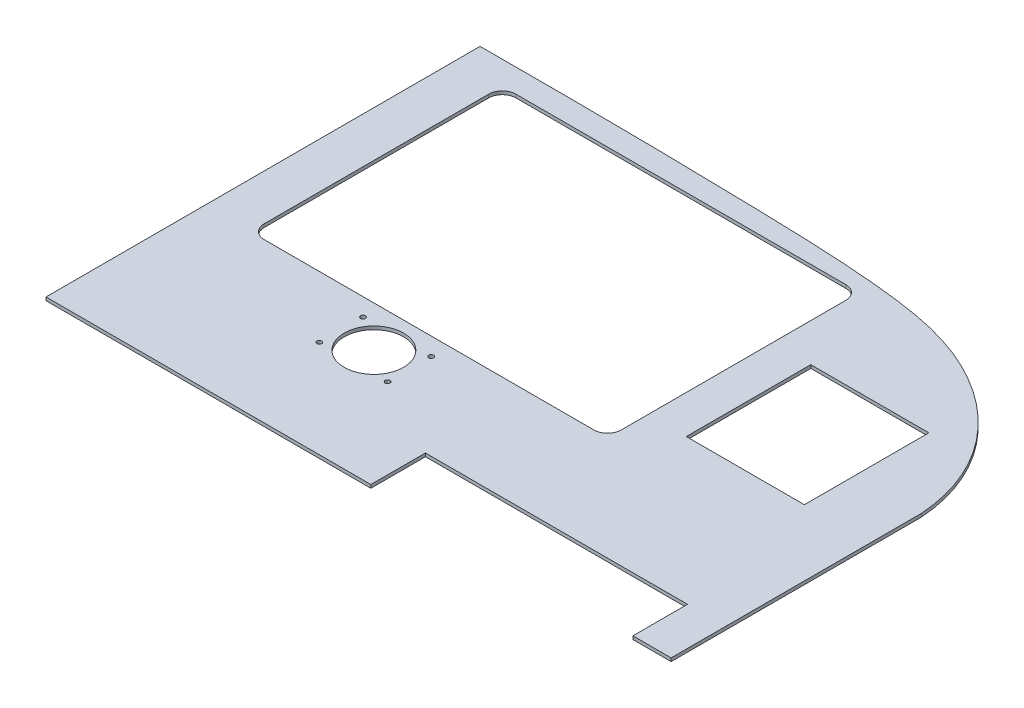
SolidWorks part; units mm, degrees
ref_plane "Alzado" through (0, 0, 0) normal (0, 0, 1) x (1, 0, 0)
ref_plane "Planta" through (0, 0, 0) normal (0, 1, 0) x (1, 0, 0)
ref_plane "Vista lateral" through (0, 0, 0) normal (1, 0, 0) x (0, 0, -1)
sketch "Croquis1" plane through (0, 0, 0) normal (0, 1, 0) x (1, 0, 0)
  line L0 (-872.7705, -164.3587) -> (-420.2125, -164.3587) construction
  line L1 (-420.2125, -164.3587) -> (-420.2125, 152.6413) construction
  line L2 (-599.3125, -124.3587) -> (-545.2125, -124.3587) construction
  line L3 (-599.3125, -124.3587) -> (-599.3125, -47.6587) construction
  line L4 (-599.3125, -47.6587) -> (-545.2125, -47.6587) construction
  line L5 (-545.2125, -124.3587) -> (-545.2125, -47.6587) construction
  line L6 (-872.7705, -164.3587) -> (-872.7705, 15.6413) construction
  line L7 (-193.9987, 152.6413) -> (-193.9987, -164.3587) construction
  line L8 (484.7732, -164.3587) -> (484.7732, 15.6413) construction
  line L9 (157.2152, -124.3587) -> (157.2152, -47.6587) construction
  line L10 (211.3152, -47.6587) -> (157.2152, -47.6587) construction
  line L11 (211.3152, -124.3587) -> (211.3152, -47.6587) construction
  line L12 (211.3152, -124.3587) -> (157.2152, -124.3587) construction
  line L13 (32.2152, -164.3587) -> (32.2152, 152.6413) construction
  line L14 (484.7732, -164.3587) -> (32.2152, -164.3587) construction
  circle A0 centre (-607.8125, -61.6587) radius 2 construction
  circle A1 centre (-537.8125, -61.6587) radius 2 construction
  circle A2 centre (-537.8125, -75.6587) radius 2 construction
  circle A3 centre (-537.8125, -89.6587) radius 2 construction
  circle A4 centre (-537.8125, -103.6587) radius 2 construction
  circle A5 centre (-537.8125, -117.6587) radius 2 construction
  circle A6 centre (-607.8125, -75.6587) radius 2 construction
  circle A7 centre (-607.8125, -89.6587) radius 2 construction
  circle A8 centre (-607.8125, -103.6587) radius 2 construction
  circle A9 centre (-607.8125, -117.6587) radius 2 construction
  circle A10 centre (219.8152, -117.6587) radius 2 construction
  circle A11 centre (219.8152, -103.6587) radius 2 construction
  circle A12 centre (219.8152, -89.6587) radius 2 construction
  circle A13 centre (219.8152, -75.6587) radius 2 construction
  circle A14 centre (149.8152, -117.6587) radius 2 construction
  circle A15 centre (149.8152, -103.6587) radius 2 construction
  circle A16 centre (149.8152, -89.6587) radius 2 construction
  circle A17 centre (149.8152, -75.6587) radius 2 construction
  circle A18 centre (149.8152, -61.6587) radius 2 construction
  circle A19 centre (219.8152, -61.6587) radius 2 construction
  spline S0 degree 3 poles (-872.7705, 15.6413) (-870.1587, 51.1179) (-859.9034, 77.3702) (-827.0825, 109.5392) (-802.8418, 124.9112) (-759.5593, 140.6884) (-735.913, 143.2787) (-720.4915, 144.8169) knots 0 0 0 0 0.358065 0.430061 0.687747 0.747962 1 1 1 1 construction
  spline S1 degree 3 poles (-420.2125, 152.6413) (-520.4329, 151.1718) (-620.5344, 152.5539) (-720.4915, 144.8169) knots 0 0 0 0 1 1 1 1 construction
  spline S2 degree 3 poles (32.2152, 152.6413) (132.4356, 151.1718) (232.5371, 152.5539) (332.4942, 144.8169) knots 0 0 0 0 1 1 1 1 construction
  spline S3 degree 3 poles (484.7732, 15.6413) (482.1614, 51.1179) (471.9061, 77.3702) (439.0852, 109.5392) (414.8445, 124.9112) (371.5619, 140.6884) (347.9157, 143.2787) (332.4942, 144.8169) knots 0 0 0 0 0.358065 0.430061 0.687747 0.747962 1 1 1 1 construction
  point P4 (-646.4915, -164.3587)
  point P67 (258.4942, -164.3587)
  dimension "D6" = 4
  dimension "D1" = 180
  dimension "D2" = 76.7
  dimension "D3" = 54.1
  dimension "D4" = 125
  dimension "D5" = 40
  dimension "D7" = 8.5
  dimension "D8" = 14
  dimension "D9" = 317
sketch "Croquis3" plane through (0, 0, 0) normal (0, 1, 0) x (1, 0, 0)
  line L0 (462.0559, -126.2441) -> (270.0559, -126.2441)
  line L2 (32.0559, -166.2441) -> (270.0559, -166.2441)
  line L4 (490.0559, -126.2441) -> (490.0559, 17.1595)
  line L5 (32.0559, -166.2441) -> (32.0559, 151.7559)
  line L10 (270.0559, -166.2441) -> (270.0559, -126.2441)
  line L23 (75.5559, 134.5812) -> (317.1836, 134.5812)
  line L24 (65.5559, 124.5812) -> (65.5559, -39.9188)
  line L25 (75.5559, -49.9188) -> (317.1836, -49.9188)
  line L26 (327.1836, 124.5812) -> (327.1836, -39.9188)
  line L27 (355.1836, 70.9559) -> (441.6836, 70.9559)
  line L28 (355.1836, 70.9559) -> (355.1836, -20.2441)
  line L29 (355.1836, -20.2441) -> (441.6836, -20.2441)
  line L30 (441.6836, 70.9559) -> (441.6836, -20.2441)
  line L31 (462.0559, -126.2441) -> (462.0559, -166.2441)
  line L32 (462.0559, -166.2441) -> (490.0559, -166.2441)
  line L33 (490.0559, -166.2441) -> (490.0559, -126.2441)
  circle A13 centre (185.9559, -79.9188) radius 21.75
  arc A14 (317.1836, -49.9188) -> (327.1836, -39.9188) centre (317.1836, -39.9188) ccw
  arc A15 (75.5559, -49.9188) -> (65.5559, -39.9188) centre (75.5559, -39.9188) cw
  arc A16 (317.1836, 134.5812) -> (327.1836, 124.5812) centre (317.1836, 124.5812) cw
  arc A17 (75.5559, 134.5812) -> (65.5559, 124.5812) centre (75.5559, 124.5812) ccw
  circle A18 centre (160.9559, -62.9188) radius 1.75
  circle A21 centre (210.9559, -62.9188) radius 1.75
  circle A22 centre (210.9559, -94.9188) radius 1.75
  circle A23 centre (160.9559, -94.9188) radius 1.75
  spline S1 degree 3 poles (32.0559, 151.7559) (102.5206, 152.0839) (202.3898, 151.1631) (322.8896, 147.2238) (425.6178, 131.8134) (485.9601, 74.2726) (490.0559, 17.1595) knots 0 0 0 0 0.404968 0.578404 0.696079 1 1 1 1
  point P0 (392.585, 125.1991)
  dimension "D7" = 25
  dimension "D14" = 43.5
  dimension "D8" = 17
  dimension "D9" = 3.5
  dimension "D2" = 318
  dimension "D3" = 220
  dimension "D4" = 40
  dimension "D5" = 458
  dimension "D6" = 40
  dimension "D10" = 2
  dimension "D13" = 28
  dimension "D11" = 30
  dimension "D12" = 33.5
  dimension "D15" = 146
  dimension "D16" = 86.5
  dimension "D17" = 91.2
  dimension "D18" = 28
extrude "Saliente-Extruir1" add sketch "Croquis3" along normal blind 2.4
